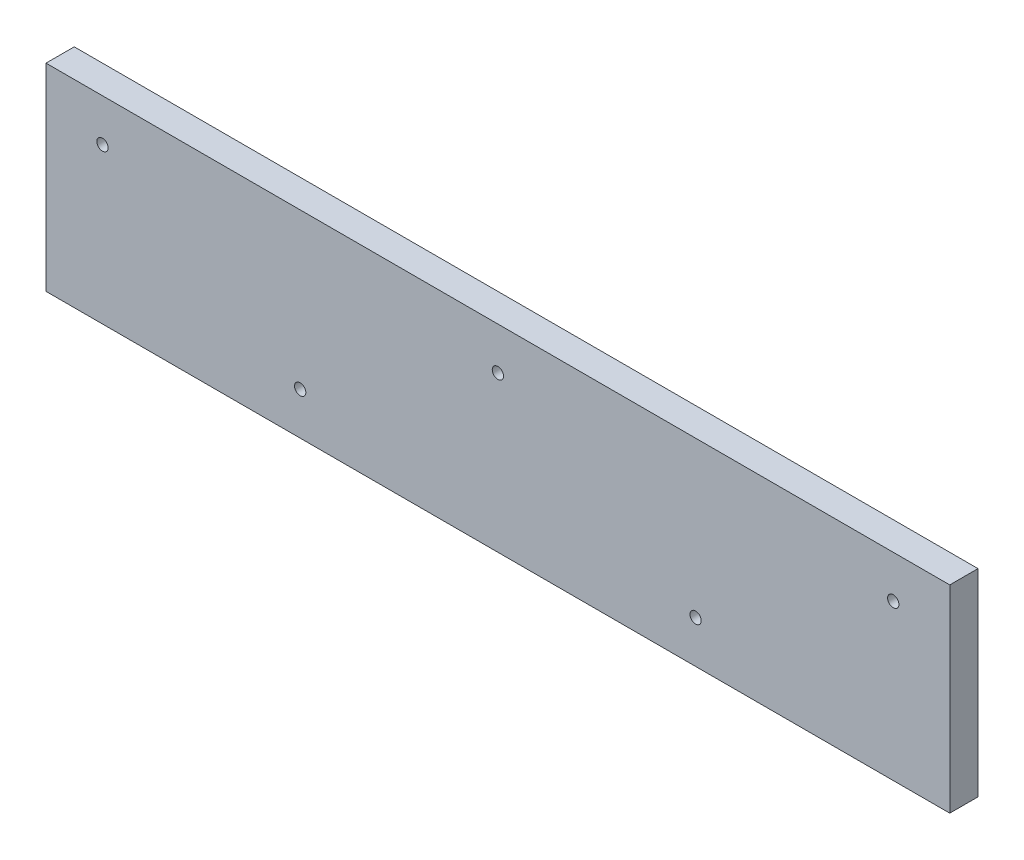
SolidWorks part; units mm, degrees
ref_plane "Plan de face" through (0, 0, 0) normal (0, 0, 1) x (1, 0, 0)
ref_plane "Plan de dessus" through (0, 0, 0) normal (0, 1, 0) x (1, 0, 0)
ref_plane "Plan de droite" through (0, 0, 0) normal (1, 0, 0) x (0, 0, -1)
sketch "Esquisse1" plane through (0, 0, 0) normal (0, 0, 1) x (1, 0, 0)
  line L1 (0, 0) -> (320, 0)
  line L2 (0, 0) -> (0, 70)
  line L3 (0, 70) -> (320, 70)
  line L4 (320, 0) -> (320, 70)
  dimension "D1" = 70
  dimension "D2" = 320
extrude "Boss.-Extru.1" add sketch "Esquisse1" along normal blind 10
sketch "Esquisse2" plane through (0, 0, 10) normal (0, 0, 1) x (1, 0, 0)
  line L0 (160, 70) -> (160, 0) construction
  line L1 (320, 70) -> (0, 70) construction
  line L2 (0, 0) -> (320, 0) construction
  line L3 (160, 55) -> (20, 55) construction
  line L4 (90, 15) -> (90, 55) construction
  line L5 (90, 35) -> (160, 35) construction
  line L6 (230, 15) -> (230, 55) construction
  circle A0 centre (160, 55) radius 2
  circle A1 centre (90, 15) radius 2
  circle A2 centre (20, 55) radius 2
  circle A3 centre (300, 55) radius 2
  circle A4 centre (230, 15) radius 2
  dimension "D1" = 4
  dimension "D2" = 140
  dimension "D3" = 40
extrude "Enlèv. mat.-Extru.1" cut sketch "Esquisse2" against normal through all both and the other way through all
